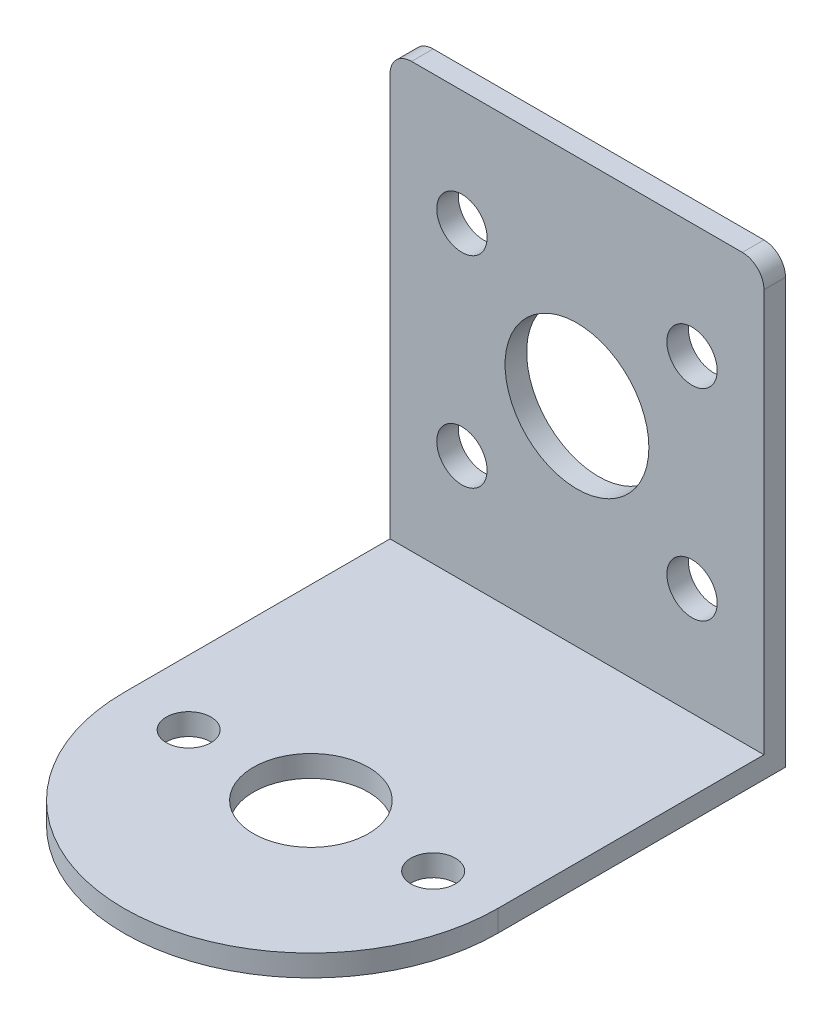
SolidWorks part; units mm, degrees
material "普通碳钢"
ref_plane "前视基准面" through (0, 0, 0) normal (0, 0, 1) x (1, 0, 0)
ref_plane "上视基准面" through (0, 0, 0) normal (0, 1, 0) x (1, 0, 0)
ref_plane "右视基准面" through (0, 0, 0) normal (1, 0, 0) x (0, 0, -1)
sketch "草图1" plane through (0, 0, 0) normal (0, 0, 1) x (1, 0, 0)
  line L1 (-13, 15.5) -> (13, 15.5)
  line L2 (-13, 15.5) -> (-13, -15.5)
  line L3 (-13, -15.5) -> (13, -15.5)
  line L4 (13, 15.5) -> (13, -15.5)
  line L5 (-13, 15.5) -> (13, -15.5) construction
  line L6 (-13, -15.5) -> (13, 15.5) construction
  point P0 (0, 0)
  dimension "D1" = 26
  dimension "D2" = 31
extrude "凸台-拉伸1" add sketch "草图1" along normal blind 1.5
sketch "草图2" plane through (0, -15.5, 0) normal (0, -1, 0) x (1, 0, 0)
  line L0 (13, 1.5) -> (13, 0) construction
  line L1 (-13, 0) -> (13, 0)
  line L2 (-13, 0) -> (-13, 20)
  line L4 (13, 0) -> (13, 20)
  arc A0 (13, 20) -> (-13, 20) centre (0, 20) ccw
  dimension "D2" = 20
extrude "凸台-拉伸2" add sketch "草图2" against normal blind 1.5
sketch "草图3" plane through (0, -15.5, 0) normal (0, -1, 0) x (1, 0, 0)
  line L0 (0, 33) -> (0, 0) construction
  circle A0 centre (0, 20) radius 4
  circle A1 centre (8.5, 20) radius 1.55
  circle A2 centre (-8.5, 20) radius 1.55
  arc A3 (13, 20) -> (-13, 20) centre (0, 20) ccw construction
  point P13 (0, 0)
  point P14 (0, 0)
  dimension "D1" = 8
  dimension "D2" = 3.1
  dimension "D3" = 3.1
  dimension "D4" = 8.5
  dimension "D5" = 8.5
extrude "切除-拉伸1" cut sketch "草图3" against normal blind 1000
fillet "圆角1" radius 1.5 2 edges at (13, 15.5, 0.75) (-13, 15.5, 0.75)
sketch "草图4" plane through (0, 0, 1.5) normal (0, 0, 1) x (1, 0, 0)
  line L0 (0, 17.2943) -> (0, -16.4715) construction
  line L2 (-14.5189, 0.5) -> (15.3975, 0.5) construction
  line L3 (11.5, 15.5) -> (-11.5, 15.5) construction
  circle A0 centre (0, 0.5) radius 5
  circle A1 centre (-8, 7.5) radius 1.75
  circle A2 centre (8, 7.5) radius 1.75
  circle A3 centre (-8, -6.5) radius 1.75
  circle A4 centre (8, -6.5) radius 1.75
  dimension "D1" = 3.5
  dimension "D2" = 3.5
  dimension "D3" = 8
  dimension "D4" = 8
  dimension "D5" = 8
  dimension "D6" = 8
  dimension "D8" = 10
  dimension "D7" = 7
extrude "切除-拉伸2" cut sketch "草图4" against normal blind 100
